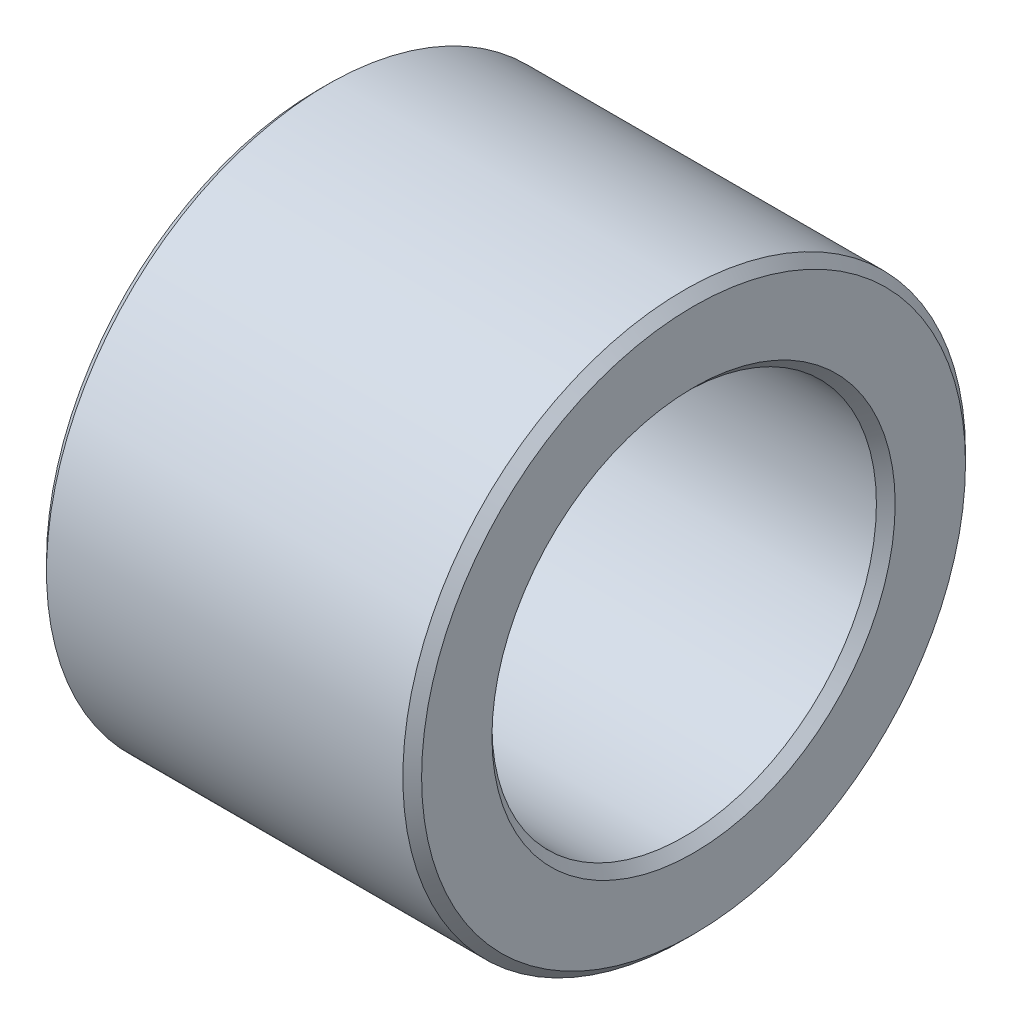
SolidWorks part; units mm, degrees
material "黄铜"
ref_plane "前视基准面" through (0, 0, 0) normal (1, 0, 0) x (0, 1, 0)
ref_plane "上视基准面" through (0, 0, 0) normal (0, 0, 1) x (0, 1, 0)
ref_plane "右视基准面" through (0, 0, 0) normal (0, 1, 0) x (-1, 0, 0)
other "Configuration Table"
sketch "草图1" plane through (0, 0, 0) normal (1, 0, 0) x (0, 1, 0)
  circle A0 centre (0, 0) radius 3
  circle A1 centre (0, 0) radius 2.05
  dimension "D1" = 6
  dimension "D2" = 4.1
extrude "凸台-拉伸1" add sketch "草图1" along normal blind 4
chamfer "倒角1" distance 0.1 angle 45 4 edges at (4, 0, -2.05) (0, 0, -2.05) (0, 0, -3) (4, 0, -3)
